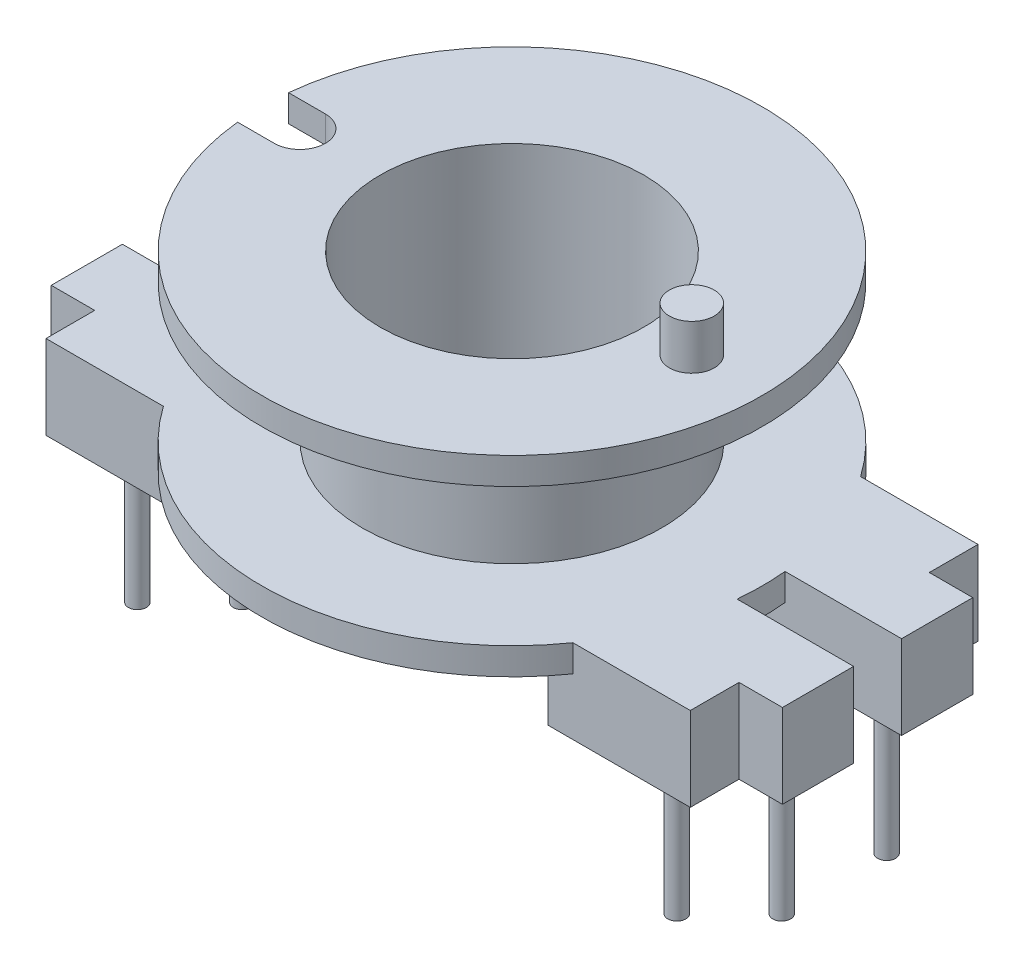
SolidWorks part; units mm, degrees
ref_plane "前视基准面" through (0, 0, 0) normal (0, 0, 1) x (1, 0, 0)
ref_plane "上视基准面" through (0, 0, 0) normal (0, 1, 0) x (1, 0, 0)
ref_plane "右视基准面" through (0, 0, 0) normal (1, 0, 0) x (0, 0, -1)
sketch "草图1" plane through (0, 0, 0) normal (0, 0, 1) x (1, 0, 0)
  line L0 (0, -3.2842) -> (0, 10.4438) construction
  line L1 (8.35, -5.5) -> (8.35, -6.4)
  line L2 (5, -0.9) -> (8.35, -0.9)
  line L3 (5, -0.9) -> (5, -5.5)
  line L4 (5, -5.5) -> (8.35, -5.5)
  line L6 (4.4, 0) -> (8.35, 0)
  line L7 (4.4, 0) -> (4.4, -6.4)
  line L8 (4.4, -6.4) -> (8.35, -6.4)
  line L9 (8.35, 0) -> (8.35, -0.9)
  dimension "D1" = 6.4
  dimension "D2" = 4.6
  dimension "D3" = 8.8
  dimension "D4" = 10
  dimension "D5" = 16.7
revolve "旋转1" add sketch "草图1" angle 360 about L0
sketch "草图2" plane through (0, 0, 0) normal (0, 1, 0) x (1, 0, 0)
  circle A0 centre (6, 0) radius 0.75
  dimension "D1" = 1.5
  dimension "D2" = 6
extrude "凸台-拉伸1" add sketch "草图2" along normal blind 1.5
sketch "草图3" plane through (0, 0, 0) normal (0, 1, 0) x (1, 0, 0)
  line L0 (-7.0784, 0) -> (-10.9837, 0) construction
  line L1 (-7.0784, -0.8513) -> (-10.9837, -0.8513)
  line L2 (-7.0784, 0.8513) -> (-10.9837, 0.8513)
  arc A0 (-7.0784, -0.8513) -> (-7.0784, 0.8513) centre (-7.0784, 0) ccw
  arc A1 (-10.9837, 0.8513) -> (-10.9837, -0.8513) centre (-10.9837, 0) ccw
  point P3 (-9.031, 0)
extrude "切除-拉伸1" cut sketch "草图3" against normal blind 1.5
sketch "草图4" plane through (0, -5.5, 0) normal (0, 1, 0) x (1, 0, 0)
  line L0 (-7.0784, 0) -> (-14.6032, 0) construction
  line L1 (-10.75, 4.8) -> (-6, 4.8)
  line L2 (-12.2, 3.175) -> (-12.2, 0.8)
  line L3 (-10.75, -4.8) -> (-6, -4.8)
  line L4 (12.2, 3.175) -> (12.2, 0.8)
  line L7 (-12.2, 3.175) -> (-10.75, 3.175)
  line L8 (-10.75, 4.8) -> (-10.75, 3.175)
  line L9 (-12.2, -3.175) -> (-10.75, -3.175)
  line L12 (-10.75, -3.175) -> (-10.75, -4.8)
  line L14 (10.75, 4.8) -> (10.75, 3.175)
  line L15 (10.75, 3.175) -> (12.2, 3.175)
  line L18 (10.75, -4.8) -> (10.75, -3.175)
  line L19 (10.75, -3.175) -> (12.2, -3.175)
  line L21 (-7.0784, -0.8) -> (-12.2, -0.8)
  line L22 (-7.0784, 0.8) -> (-12.2, 0.8)
  line L23 (7.0784, 0) -> (12.2, 0) construction
  line L24 (7.0784, 0.8) -> (12.2, 0.8)
  line L25 (7.0784, -0.8) -> (12.2, -0.8)
  line L26 (0, 7.9952) -> (0, -9.0787) construction
  line L28 (-6, 4.8) -> (-6, -4.8)
  line L30 (6, 4.8) -> (6, -4.8)
  line L31 (-2.7682, 0) -> (3.2088, 0) construction
  line L32 (12.2, -0.8) -> (12.2, -3.175)
  line L33 (-12.2, -0.8) -> (-12.2, -3.175)
  line L34 (6, 4.8) -> (10.75, 4.8)
  line L35 (6, -4.8) -> (10.75, -4.8)
  arc A0 (-7.0784, -0.8) -> (-7.0784, 0.8) centre (-7.0784, 0) ccw
  arc A2 (7.0784, 0.8) -> (7.0784, -0.8) centre (7.0784, 0) ccw
  point P24 (-10.8408, 0)
  point P29 (10.8765, 0)
  dimension "D1" = 12
  dimension "D2" = 24.4
  dimension "D3" = 9.6
  dimension "D4" = 21.5
  dimension "D5" = 6.35
  dimension "D6" = 1.6
extrude "凸台-拉伸2" add sketch "草图4" against normal blind 2.8
sketch "草图5" plane through (0, -8.3, 0) normal (0, -1, 0) x (1, 0, 0)
  line L0 (-13.7181, 0) -> (17.5224, 0) construction
  line L1 (-10.75, 1.75) -> (10.75, 1.75) construction
  line L2 (-10.75, 1.75) -> (-10.75, -1.75) construction
  line L3 (-10.75, -1.75) -> (10.75, -1.75) construction
  line L4 (10.75, 1.75) -> (10.75, -1.75) construction
  line L5 (-9, 3.5) -> (9, 3.5) construction
  line L6 (-9, 3.5) -> (-9, -3.5) construction
  line L7 (-9, -3.5) -> (9, -3.5) construction
  line L8 (9, 3.5) -> (9, -3.5) construction
  line L9 (0, -9.5106) -> (0, 9.9811) construction
  line L11 (-7.25, 1.75) -> (7.25, 1.75) construction
  line L12 (-7.25, 1.75) -> (-7.25, -1.75) construction
  line L13 (-7.25, -1.75) -> (7.25, -1.75) construction
  line L14 (7.25, 1.75) -> (7.25, -1.75) construction
  circle A0 centre (-10.75, -1.75) radius 0.3
  circle A1 centre (-7.25, -1.75) radius 0.3
  circle A2 centre (-9, -3.5) radius 0.3
  circle A3 centre (-9, 3.5) radius 0.3
  circle A4 centre (-10.75, 1.75) radius 0.3
  circle A5 centre (-7.25, 1.75) radius 0.3
  circle A6 centre (7.25, 1.75) radius 0.3
  circle A7 centre (10.75, 1.75) radius 0.3
  circle A8 centre (10.75, -1.75) radius 0.3
  circle A9 centre (7.25, -1.75) radius 0.3
  circle A10 centre (9, -3.5) radius 0.3
  circle A11 centre (9, 3.5) radius 0.3
  point P33 (0, 0)
  point P36 (0, 0)
  point P37 (0, 0)
  point P38 (0, 0)
  point P39 (0, 0)
  point P40 (0, 0)
  point P41 (-9, 2.6771)
  dimension "D1" = 21.5
  dimension "D3" = 7
  dimension "D4" = 0.6
  dimension "D5" = 18
  dimension "D6" = 14.5
  dimension "D2" = 3.5
extrude "凸台-拉伸3" add sketch "草图5" along normal blind 4.6
